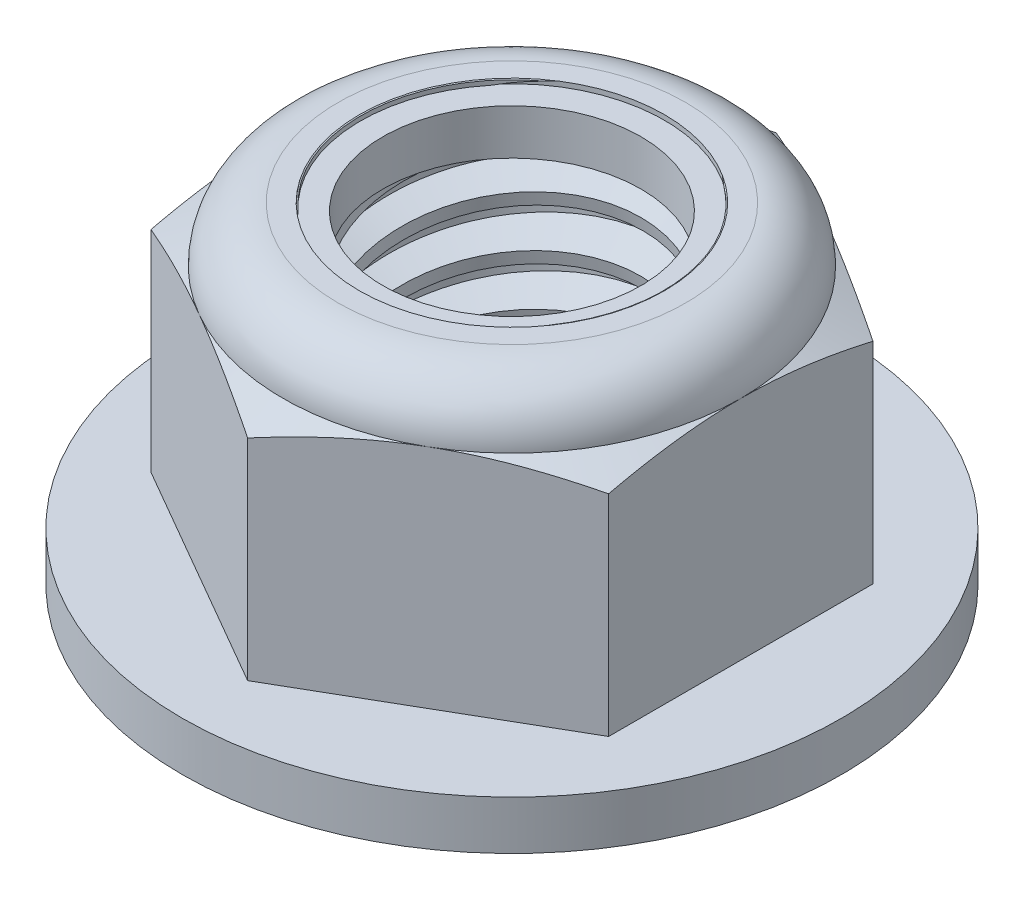
SolidWorks part; units mm, degrees
ref_plane "Front" through (0, 0, 0) normal (0, 0, 1) x (1, 0, 0)
ref_plane "Top" through (0, 0, 0) normal (0, 1, 0) x (1, 0, 0)
ref_plane "Right" through (0, 0, 0) normal (1, 0, 0) x (0, 0, -1)
sketch "Sketch1" plane through (0, 0, 0) normal (0, 1, 0) x (1, 0, 0)
  line L1 (0, 8.2489) -> (-7.1438, 4.1244)
  line L2 (-7.1438, 4.1244) -> (-7.1438, -4.1244)
  line L3 (-7.1438, -4.1244) -> (0, -8.2489)
  line L4 (0, -8.2489) -> (7.1437, -4.1244)
  line L5 (7.1437, -4.1244) -> (7.1437, 4.1244)
  line L6 (7.1437, 4.1244) -> (0, 8.2489)
  circle A0 centre (0, 0) radius 7.1438 construction
  dimension "Hex Flats" = 14.2875
extrude "Extrude1" add sketch "Sketch1" along normal blind 10.3187
sketch "Sketch8" plane through (0, 0, 0) normal (1, 0, 0) x (0, 0, -1)
  line L0 (0, 0) -> (10.287, 0)
  line L1 (10.287, 0) -> (10.287, 1.524)
  line L2 (10.287, 1.524) -> (0, 1.524)
  line L3 (0, 1.524) -> (0, 0)
  line L4 (0, 0) -> (0, -1.524) construction
  dimension "Flange Height" = 1.524
  dimension "Flange Dia" = 20.574
revolve "Revolve3" add sketch "Sketch8" angle 360 about L4
sketch "Sketch2" plane through (0, 0, 0) normal (1, 0, 0) x (0, 0, -1)
  line L0 (-4.7625, 0) -> (-4.7625, 10.3187) construction
  line L1 (0, 0) -> (4.7625, 0)
  line L2 (0, 0) -> (0, 10.3187)
  line L3 (0, 10.3187) -> (4.7625, 10.3187)
  line L4 (4.7625, 0) -> (4.7625, 10.3187)
  line L5 (-4.1244, 10.3187) -> (4.1244, 10.3187) construction
  line L7 (0, -4.7625) -> (0, 0) construction
  dimension "Thread Dia" = 9.525
revolve "Revolve1" add sketch "Sketch2" angle 360 about L7
sketch "Sketch3" plane through (0, 0, 0) normal (1, 0, 0) x (0, 0, -1)
  line L0 (4.7625, 10.3188) -> (-4.7625, 10.3187) construction
  line L1 (-4.7625, 10.3187) -> (-4.7625, 8.7312) construction
  line L2 (-4.7625, 8.7312) -> (4.7625, 10.3188) construction
  line L3 (4.7625, 10.3188) -> (4.7951, 10.123) construction
  line L4 (4.7951, 10.123) -> (5.0235, 8.7528)
  line L5 (5.0235, 8.7528) -> (4.0944, 9.1009)
  line L6 (4.0944, 9.1009) -> (4.0291, 9.4924)
  line L7 (4.0291, 9.4924) -> (4.7951, 10.123)
  line L8 (4.0617, 9.2967) -> (4.9093, 9.4379) construction
  line L9 (4.7625, 10.3188) -> (4.7625, 9.4135) construction
  line L10 (4.7625, 9.4135) -> (-4.7625, 7.826) construction
  line L11 (-4.7625, 7.826) -> (-4.7625, 8.7312) construction
  line L12 (-0.2832, 10.3187) -> (0.2832, 6.9207) construction
  line L13 (-4.7625, 0) -> (-4.7625, 10.3187) construction
  line L14 (0, 10.3187) -> (4.7625, 10.3187) construction
  line L15 (4.7625, 0) -> (4.7625, 10.3187) construction
  point P13 (0, 8.6197)
  dimension "D1" = 0.1984
  dimension "D2" = 0.3969
  dimension "Thread Pitch" = 1.5875
  dimension "D4" = 60
  dimension "D5" = 1.5875
revolve "Cut-Revolve1" cut sketch "Sketch3" angle 360 about L12
pattern_linear "LPattern1" count 7 spacing 1.5875 along (0, -1, 0) count 2 spacing 1.5875 along (0, 1, 0) of "Cut-Revolve1"
sketch "Sketch4" plane through (0, 0, 0) normal (1, 0, 0) x (0, 0, -1)
  line L0 (0, 10.3187) -> (4.7625, 10.3187)
  line L1 (4.7625, 10.3187) -> (4.0291, 9.9768)
  line L2 (4.0291, 9.9768) -> (4.0291, 0.342)
  line L3 (4.0291, 0.342) -> (4.7625, 0)
  line L4 (4.7625, 0) -> (0, 0)
  line L5 (0, 0) -> (0, 10.3187)
  line L6 (4.7625, 0) -> (4.7625, 10.3187) construction
  line L7 (0, 10.3187) -> (4.7625, 10.3187) construction
  line L8 (0, 0) -> (4.7625, 0) construction
  line L9 (0, 0) -> (0, 10.3187) construction
  line L10 (0, 10.3187) -> (0, 11.128) construction
  dimension "D1" = 25
revolve "Cut-Revolve2" cut sketch "Sketch4" angle 360 about L10
combine bodies "Combine1" operation type subtract main body 112 bodies to subtract 111
sketch "Sketch5" plane through (0, 0, 0) normal (1, 0, 0) x (0, 0, -1)
  line L0 (10.287, 1.524) -> (0, 1.524) construction
  line L1 (0, 0) -> (10.287, 0) construction
  line L2 (8.2489, 1.524) -> (8.2489, 8.0836)
  line L3 (8.2489, 8.0836) -> (7.1438, 8.599)
  line L4 (5.424, 10.3188) -> (5.424, 11.5888)
  line L5 (5.424, 11.5888) -> (9.5189, 11.5888)
  line L6 (9.5189, 11.5888) -> (9.5189, 1.524)
  line L9 (7.1438, 8.599) -> (7.1438, 0) construction
  line L13 (8.2489, 1.524) -> (9.5189, 1.524)
  line L15 (0, 0) -> (0, 11.5888) construction
  line L20 (0, 11.5888) -> (5.424, 11.5888) construction
  line L22 (0, 10.3187) -> (4.7625, 10.3187) construction
  arc A0 (7.1438, 8.599) -> (5.424, 10.3188) centre (5.424, 8.599) ccw
  dimension "D4" = 1.7198
  dimension "D1" = 1.27
  dimension "D2" = 115
  dimension "D3" = 10.3188
revolve "Cut-Revolve3" cut sketch "Sketch5" angle 360 about L15
sketch "Sketch6" plane through (0, 0, 0) normal (1, 0, 0) x (0, 0, -1)
  line L0 (0, 8.599) -> (6.9914, 8.599)
  line L1 (5.424, 10.1664) -> (4.7265, 10.1664)
  line L2 (0, 11.5888) -> (0, 8.599)
  line L3 (4.7265, 11.5888) -> (0, 11.5888)
  line L4 (0, 11.5888) -> (5.424, 11.5888) construction
  line L5 (0, 0) -> (0, 11.5888) construction
  line L6 (0, 11.5888) -> (0, 44.323) construction
  line L7 (4.7265, 10.1664) -> (4.7265, 11.5888)
  line L8 (5.424, 10.3188) -> (5.424, 10.1664) construction
  line L9 (4.7265, 10.1664) -> (4.0291, 10.1664) construction
  line L10 (4.0291, 10.1664) -> (4.0291, 9.9768) construction
  arc A0 (6.9914, 8.599) -> (5.424, 10.1664) centre (5.424, 8.599) ccw
  arc A1 (7.1438, 8.599) -> (5.424, 10.3188) centre (5.424, 8.599) ccw construction
  dimension "D1" = 0.1524
revolve "Cut-Revolve4" cut sketch "Sketch6" angle 360 about L6
sketch "Sketch7" plane through (0, 0, 0) normal (1, 0, 0) x (0, 0, -1)
  line L0 (4.0291, 8.6752) -> (6.9132, 8.6752)
  line L1 (5.424, 10.0902) -> (4.0291, 10.0901)
  line L2 (4.0291, 10.0901) -> (4.0291, 8.6752)
  line L3 (4.0291, 8.6752) -> (0, 8.6752) construction
  line L4 (0, 8.6752) -> (0, 10.0902) construction
  line L5 (0, 10.0902) -> (4.0291, 10.0901) construction
  line L6 (4.0291, 8.6752) -> (4.0291, 8.599) construction
  line L7 (0, 8.599) -> (6.9914, 8.599) construction
  line L8 (5.424, 10.0902) -> (5.424, 10.1664) construction
  arc A0 (6.9132, 8.6752) -> (5.424, 10.0902) centre (5.424, 8.599) ccw
  arc A2 (6.9914, 8.599) -> (5.424, 10.1664) centre (5.424, 8.599) ccw construction
  dimension "D1" = 0.0762
revolve "Revolve2" add sketch "Sketch7" angle 360 about L4
equation "\"D1@Sketch3\"=\"Thread Pitch@Sketch3\"/8"
equation "\"D2@Sketch3\"=\"Thread Pitch@Sketch3\"/4"
equation "\"D5@Sketch3\"=\"Thread Pitch@Sketch3\""
equation "\"D4@LPattern1\"=\"Thread Pitch@Sketch3\""
equation "\"D3@LPattern1\"=\"Thread Pitch@Sketch3\""
equation "\"D1@LPattern1\"=\"Height@Extrude1\"/\"Thread Pitch@Sketch3\""
equation "\"D4@Sketch5\"=\"Height@Extrude1\"/6"
